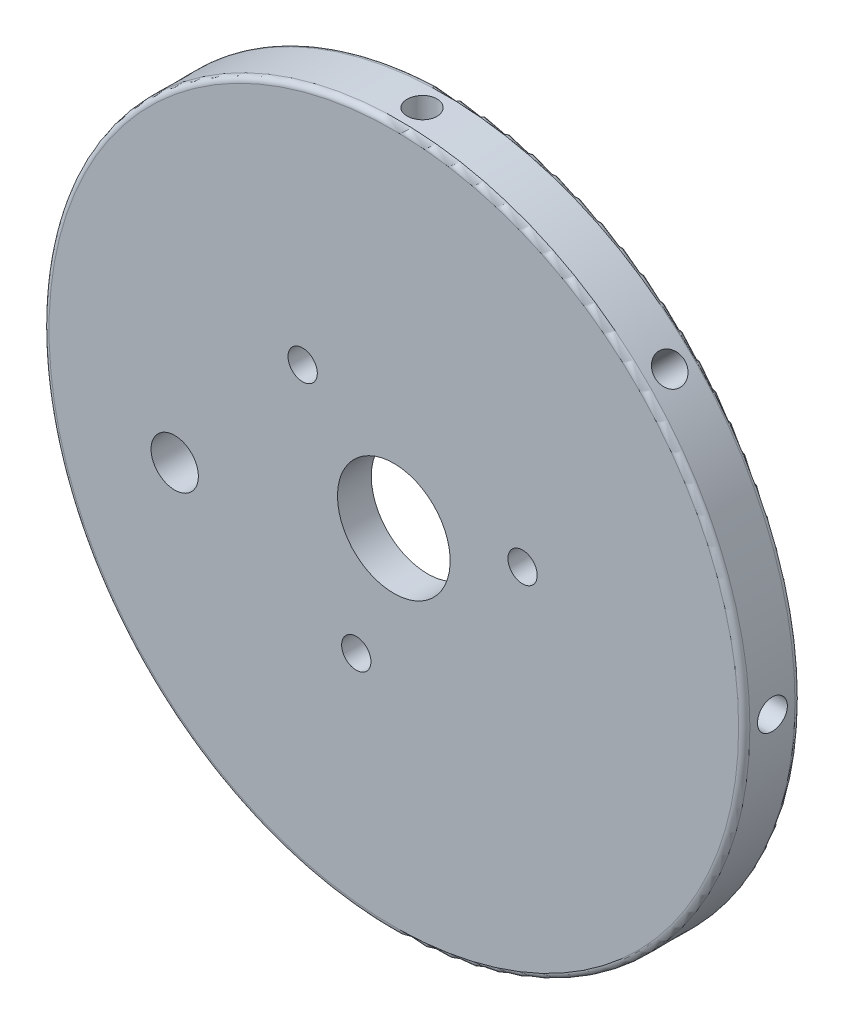
SolidWorks part; units mm, degrees
material "7075-T6 (SN)"
ref_plane "Ön Düzlem" through (0, 0, 0) normal (0, 0, 1) x (1, 0, 0)
ref_plane "Üst Düzlem" through (0, 0, 0) normal (0, 1, 0) x (1, 0, 0)
ref_plane "Sağ Düzlem" through (0, 0, 0) normal (1, 0, 0) x (0, 0, -1)
sketch "Çizim1" plane through (0, 0, 0) normal (0, 0, 1) x (1, 0, 0)
  circle A0 centre (0, 0) radius 62.2
  dimension "D1" = 124.4
extrude "Yükseklik-Ekstrüzyon1" add sketch "Çizim1" along normal blind 10
fillet "Radyus1" radius 1 2 edges at (62.2, 0, 10) (62.2, 0, 0)
sketch "Çizim2" plane through (0, 0, 0) normal (0, 0, -1) x (-1, 0, 0)
  circle A0 centre (0, 0) radius 10
  dimension "D1" = 20
extrude "Kes-Ekstrüzyon1" cut sketch "Çizim2" against normal blind 10
sketch "Çizim8" plane through (0, 0, 0) normal (0, 0, -1) x (-1, 0, 0)
  line L1 (-22.8483, 5.4959) -> (6.6645, -22.5352) construction
  line L2 (6.6645, -22.5352) -> (16.1838, 17.0392) construction
  line L3 (16.1838, 17.0392) -> (-22.8483, 5.4959) construction
  circle A0 centre (0, 0) radius 11.75 construction
  circle A1 centre (16.1838, 17.0392) radius 2.6
  circle A2 centre (6.6645, -22.5352) radius 2.6
  circle A3 centre (-22.8483, 5.4959) radius 2.6
  dimension "D2" = 5.2
  dimension "D3" = 5.2
  dimension "D4" = 5.2
  dimension "D1" = 23.5
extrude "Kes-Ekstrüzyon5" cut sketch "Çizim8" against normal blind 10
sketch "Çizim9" plane through (0, 0, 10) normal (0, 0, 1) x (1, 0, 0)
  line L0 (0, 0) -> (-16.1838, 17.0392) construction
  line L1 (0, 0) -> (-38.8907, -9.3548) construction
  circle A0 centre (-38.8907, -9.3548) radius 2.9
  dimension "D3" = 5.8
  dimension "D1" = 60
  dimension "D2" = 40
sketch "Çizim10" plane through (0, 0, 0) normal (0, 0, -1) x (-1, 0, 0)
  circle A0 centre (0, 0) radius 29
  dimension "D1" = 58
extrude "Kes-Ekstrüzyon7" cut sketch "Çizim10" against normal blind 4
ref_plane "Düzlem1" through (0, 62.2, 0) normal (0, 1, 0) x (1, 0, 0)
hole_wizard "M8 Boşluklu Delik1" positions "3B Çizim1" profile "Çizim14" hole size "M8" standard "ISO" end condition through all
sketch3d "3B Çizim1"
  point P0 (-38.8907, -9.3548, 10)
sketch "Çizim14" plane through (-38.8907, -9.3548, 10) normal (1, 0, 0) x (0, -1, 0)
  line L0 (0, 0) -> (0, 10)
  line L1 (0, 10) -> (4.2, 10)
  line L2 (4.2, 10) -> (4.2, 0)
  line L5 (4.2, 0) -> (0, 0)
  line L11 (0, -6.35) -> (0, 107.95) construction
  dimension "Thru Hole Dia." = 8.4
  dimension "Thru Hole Depth" = 10
sketch "Çizim15" plane through (0, 62.2, 0) normal (0, 1, 0) x (1, 0, 0)
  line L0 (62.2, -1) -> (-62.2, -1) construction
  circle A0 centre (0, -5) radius 2.5
  point P0 (0, -5)
  dimension "D1" = 5
  dimension "D2" = 4
hole_wizard "M5 Boşluklu Delik1" positions "Çizim15" profile "Çizim18" hole size "M5" standard "ISO"
sketch "Çizim18" plane through (0, 62.2, 5) normal (1, 0, 0) x (0, 0, 1)
  line L0 (0, 0) -> (0, 14.1923)
  line L1 (0, 14.1923) -> (2.65, 12.6)
  line L2 (2.65, 12.6) -> (2.65, 0)
  line L5 (2.65, 0) -> (0, 0)
  line L10 (0, 14.1923) -> (-2.65, 12.6) construction
  line L11 (0, -6.35) -> (0, 107.95) construction
  dimension "Hole Dia." = 5.3
  dimension "Hole Depth" = 12.6
  dimension "Drill Angle" = 118
pattern_circular "Dairesel Kaplama1" count 8 over 360 about axis through (0, 0, 10) along (0, 0, -1) of "M5 Boşluklu Delik1"
